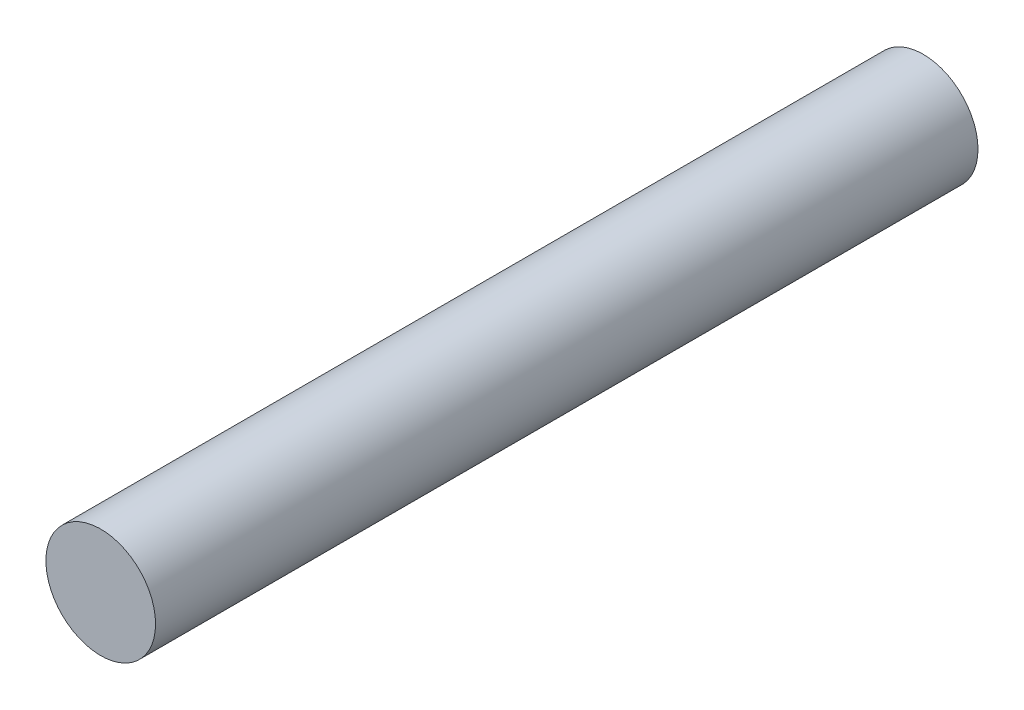
SolidWorks part; units mm, degrees
ref_plane "Plano frontal" through (0, 0, 0) normal (0, 0, 1) x (1, 0, 0)
ref_plane "Plano superior" through (0, 0, 0) normal (0, 1, 0) x (1, 0, 0)
ref_plane "Plano direito" through (0, 0, 0) normal (1, 0, 0) x (0, 0, -1)
sketch "Esboço1" plane through (0, 0, 0) normal (0, 0, 1) x (1, 0, 0)
  circle A0 centre (0, 0) radius 5
  dimension "D1" = 10
extrude "Ressalto-extrusão1" add sketch "Esboço1" along normal blind 75
